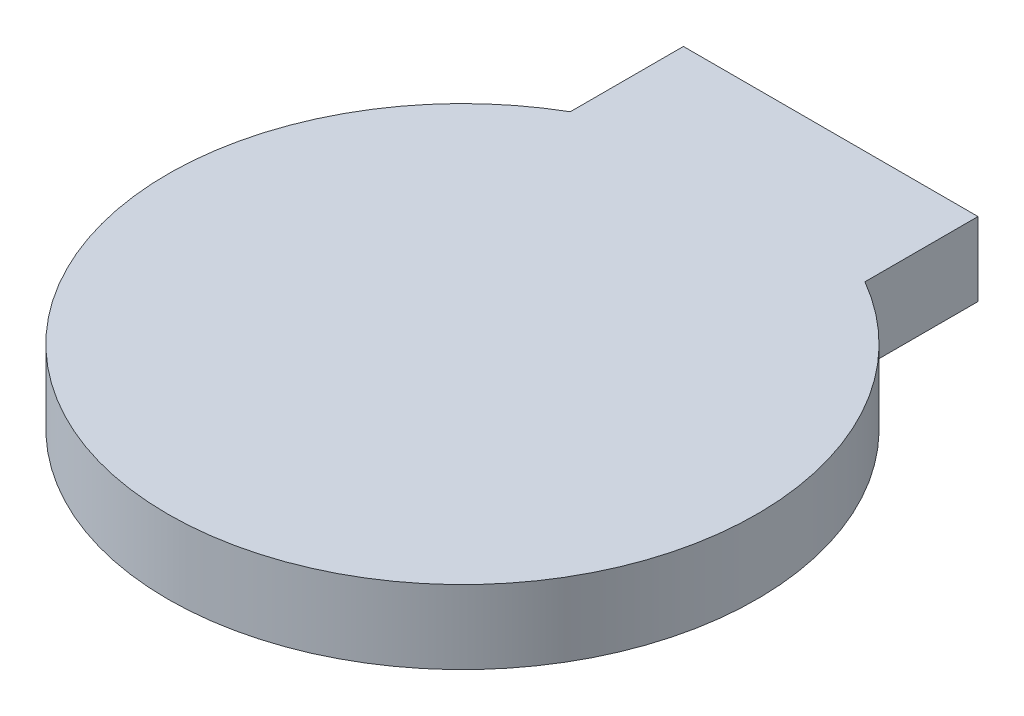
SolidWorks part; units mm, degrees
ref_plane "Alzado" through (0, 0, 0) normal (0, 0, 1) x (1, 0, 0)
ref_plane "Planta" through (0, 0, 0) normal (0, 1, 0) x (1, 0, 0)
ref_plane "Vista lateral" through (0, 0, 0) normal (1, 0, 0) x (0, 0, -1)
sketch "Croquis1" plane through (0, 0, 0) normal (0, 1, 0) x (1, 0, 0)
  line L1 (-6, 15) -> (6, 15)
  line L2 (-6, 15) -> (-6, 10.3923)
  line L4 (6, 15) -> (6, 10.3923)
  arc A0 (-6, 10.3923) -> (6, 10.3923) centre (0, 0) ccw
  dimension "D1" = 24
  dimension "D2" = 12
  dimension "D3" = 6
  dimension "D4" = 15
extrude "Saliente-Extruir1" add sketch "Croquis1" along normal blind 3
